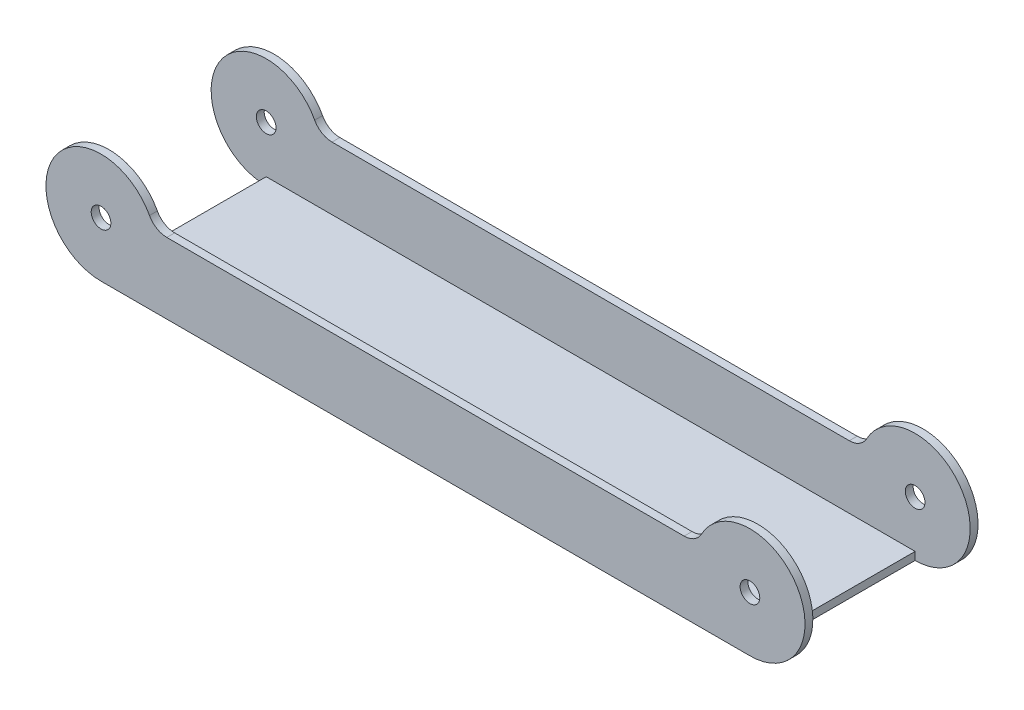
SolidWorks part; units mm, degrees
ref_plane "Front Plane" through (0, 0, 0) normal (0, 0, 1) x (1, 0, 0)
ref_plane "Top Plane" through (0, 0, 0) normal (0, 1, 0) x (1, 0, 0)
ref_plane "Right Plane" through (0, 0, 0) normal (1, 0, 0) x (0, 0, -1)
sketch "Sketch2" plane through (0, 0, 0) normal (0, 1, 0) x (1, 0, 0)
  line L1 (-97.5, 22) -> (97.5, 22)
  line L2 (-97.5, 22) -> (-97.5, -22)
  line L3 (-97.5, -22) -> (97.5, -22)
  line L4 (97.5, 22) -> (97.5, -22)
  line L5 (-97.5, 22) -> (97.5, -22) construction
  line L6 (-97.5, -22) -> (97.5, 22) construction
  point P0 (0, 0)
  dimension "D1" = 44
  dimension "D2" = 195
extrude "Boss-Extrude1" add sketch "Sketch2" along normal mid plane 28
shell "Shell1" thickness 2
sketch "Sketch3" plane through (0, 0, 22) normal (0, 0, 1) x (1, 0, 0)
  circle A0 centre (-82.5, 0) radius 2.5
  circle A1 centre (82.5, 0) radius 2.5
  dimension "D1" = 5
  dimension "D2" = 165
  dimension "D3" = 82.5
extrude "Cut-Extrude1" cut sketch "Sketch3" against normal through all
sketch "Sketch4" plane through (-95.5, 0, 0) normal (1, 0, 0) x (0, 0, -1)
  line L4 (-20, -12) -> (20, -12)
  line L5 (20, -12) -> (20, 14)
  line L6 (20, 14) -> (-20, 14)
  line L7 (-20, 14) -> (-20, -12)
  line L8 (-20, -12) -> (20, -12)
  line L9 (20, -12) -> (20, 14)
  line L10 (20, 14) -> (-20, 14)
  line L11 (-20, 14) -> (-20, -12)
  dimension "D1" = 0
extrude "Cut-Extrude2" cut sketch "Sketch4" against normal up to next and the other way up to next
sketch "Sketch6" plane through (0, 0, 0) normal (0, 0, 1) x (1, 0, 0)
  line L0 (-69.0836, 4) -> (69.0836, 4)
  line L1 (-97.5, 14) -> (97.5, 14) construction
  line L2 (97.5, 14) -> (97.5, -14) construction
  line L3 (-97.5, 14) -> (-97.5, -14) construction
  line L4 (-97.5, -14) -> (97.5, -14) construction
  line L5 (97.5, 24) -> (97.5, -14)
  line L7 (-97.5, 24) -> (-97.5, -14)
  line L8 (-97.5, -14) -> (-82.5, -14)
  line L9 (82.5, -14) -> (97.5, -14)
  line L10 (-97.5, 24) -> (97.5, 24)
  arc A0 (-69.0836, 4) -> (-82.5, -14) centre (-82.5, 0) ccw
  arc A1 (82.5, -14) -> (69.0836, 4) centre (82.5, 0) ccw
  dimension "D1" = 28
  dimension "D2" = 28
  dimension "D3" = 10
  dimension "D4" = 20
extrude "Cut-Extrude3" cut sketch "Sketch6" against normal through all both and the other way through all
sketch "Sketch7" plane through (0, -14, 0) normal (0, -1, 0) x (1, 0, 0)
  line L0 (82.5, -22) -> (82.5, 22) construction
  line L1 (89.7111, 20) -> (82.5, 20)
  line L2 (89.7111, 20) -> (89.7111, -20)
  line L3 (89.7111, -20) -> (82.5, -20)
  line L4 (82.5, 20) -> (82.5, -20)
  line L5 (-82.5, -22) -> (-82.5, 22) construction
  line L6 (-89.7111, 20) -> (-82.5, 20)
  line L7 (-89.7111, 20) -> (-89.7111, -20)
  line L8 (-89.7111, -20) -> (-82.5, -20)
  line L9 (-82.5, 20) -> (-82.5, -20)
extrude "Cut-Extrude4" cut sketch "Sketch7" against normal up to next
fillet "Fillet1" radius 5 4 edges at (69.0836, 4, -21) (69.0836, 4, 21) (-69.0836, 4, 21) (-69.0836, 4, -21)
